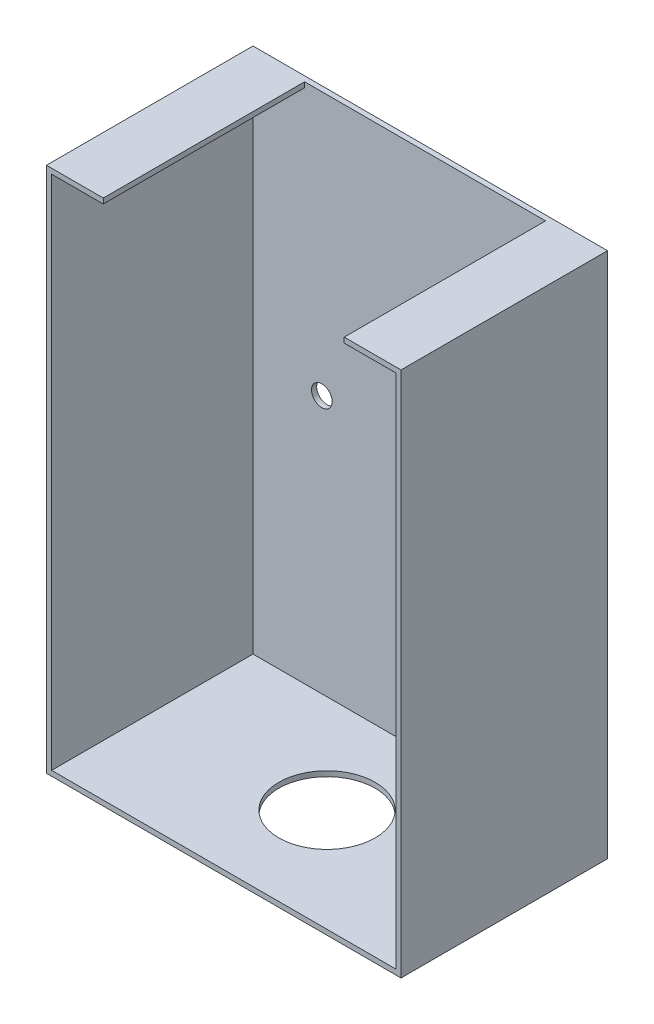
SolidWorks part; units mm, degrees
ref_plane "Front Plane" through (0, 0, 0) normal (0, 0, 1) x (1, 0, 0)
ref_plane "Top Plane" through (0, 0, 0) normal (0, 1, 0) x (1, 0, 0)
ref_plane "Right Plane" through (0, 0, 0) normal (1, 0, 0) x (0, 0, -1)
sketch "Sketch1" plane through (0, 0, 0) normal (0, 0, 1) x (1, 0, 0)
  line L1 (51.5, -76.5) -> (-51.5, -76.5)
  line L2 (51.5, -76.5) -> (51.5, 76.5)
  line L3 (51.5, 76.5) -> (-51.5, 76.5)
  line L4 (-51.5, -76.5) -> (-51.5, 76.5)
  line L5 (51.5, -76.5) -> (-51.5, 76.5) construction
  line L6 (51.5, 76.5) -> (-51.5, -76.5) construction
  point P0 (0, 0)
  dimension "D1" = 103
  dimension "D2" = 153
extrude "Boss-Extrude1" add sketch "Sketch1" along normal blind 60
shell "Shell1" thickness 1.5
sketch "Sketch2" plane through (0, -76.5, 0) normal (0, -1, 0) x (1, 0, 0)
  line L0 (0, 0) -> (0, 60) construction
  line L1 (-51.5, 0) -> (51.5, 0) construction
  line L2 (-51.5, 60) -> (51.5, 60) construction
  circle A0 centre (0, 30) radius 14
  dimension "D1" = 28
extrude "Cut-Extrude1" cut sketch "Sketch2" against normal up to next
sketch "Sketch3" plane through (50, 0, 0) normal (-1, 0, 0) x (0, 0, 1)
  line L0 (60, 76.5) -> (60, -76.5) construction
  line L1 (1.5, 76.5) -> (60, 76.5)
  line L2 (1.5, 76.5) -> (1.5, 75)
  line L3 (1.5, 75) -> (60, 75)
  line L4 (60, 76.5) -> (60, 75)
  dimension "D1" = 1.5
extrude "Boss-Extrude2" add sketch "Sketch3" along normal blind 15
mirror "Mirror1" about plane through (0, 0, 0) normal (1, 0, 0) of "Boss-Extrude2"
sketch "Sketch4" plane through (0, 0, 0) normal (0, 0, -1) x (-1, 0, 0)
  line L0 (0, 76.5) -> (0, -76.5) construction
  line L1 (-51.5, 76.5) -> (51.5, 76.5) construction
  line L2 (51.5, -76.5) -> (-51.5, -76.5) construction
  line L3 (-30, 76.5) -> (-30, -76.5) construction
  line L4 (30, 76.5) -> (30, -76.5) construction
  circle A0 centre (-30, 0) radius 3
  circle A1 centre (30, 0) radius 3
  dimension "D1" = 6
  dimension "D2" = 60
extrude "Cut-Extrude2" cut sketch "Sketch4" against normal up to next
